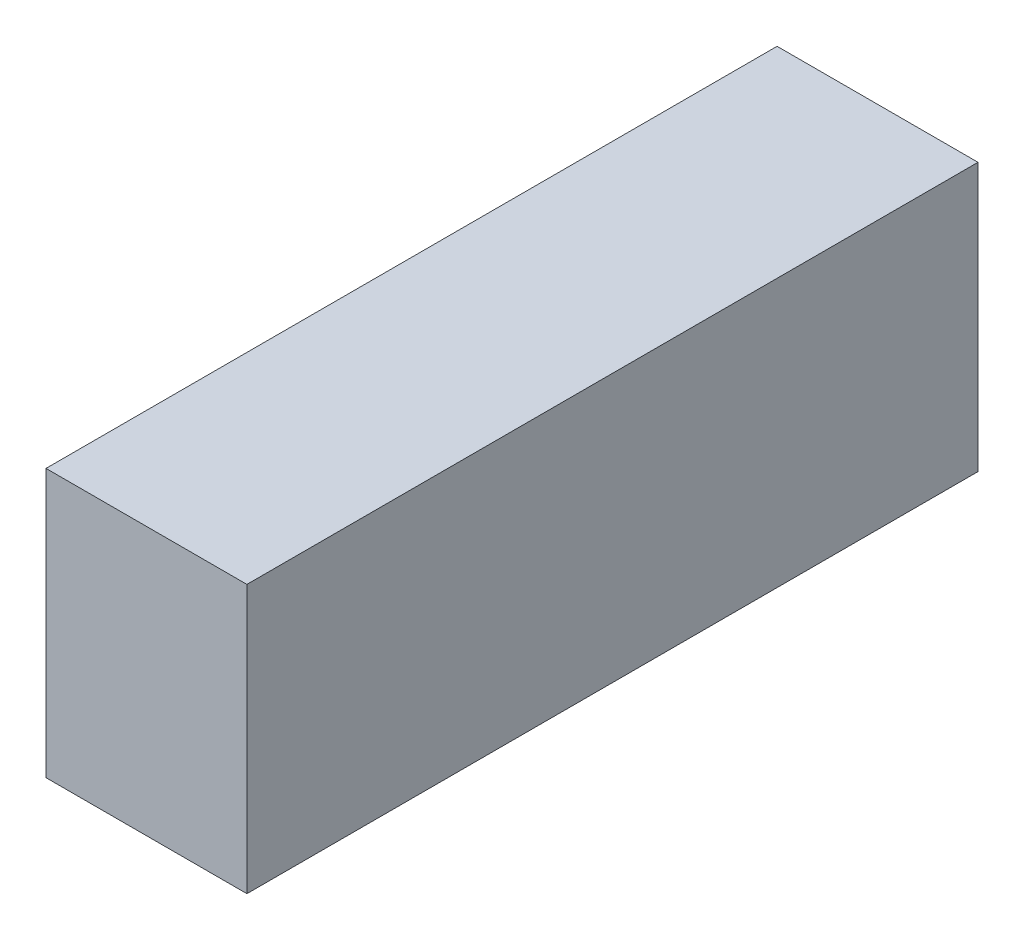
SolidWorks part; units mm, degrees
ref_plane "Front Plane" through (0, 0, 0) normal (0, 0, 1) x (1, 0, 0)
ref_plane "Top Plane" through (0, 0, 0) normal (0, 1, 0) x (1, 0, 0)
ref_plane "Right Plane" through (0, 0, 0) normal (1, 0, 0) x (0, 0, -1)
sketch "Sketch4" plane through (0, 0, 0) normal (0, 0, 1) x (1, 0, 0)
  line L1 (175.8701, 113.0552) -> (61.5701, 113.0552)
  line L2 (175.8701, 113.0552) -> (175.8701, -39.3448)
  line L3 (175.8701, -39.3448) -> (61.5701, -39.3448)
  line L4 (61.5701, 113.0552) -> (61.5701, -39.3448)
extrude "Boss-Extrude1" add sketch "Sketch4" along normal blind 415.925
